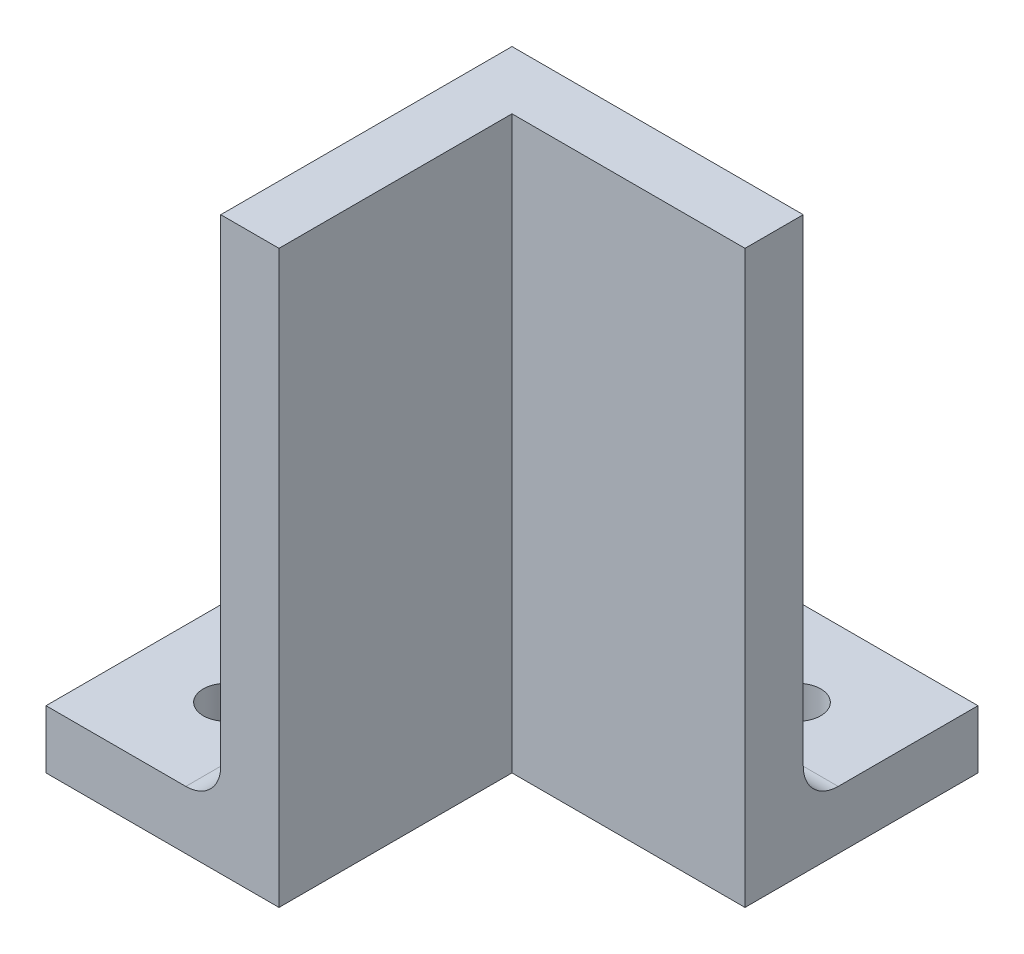
SolidWorks part; units mm, degrees
ref_plane "Front Plane" through (0, 0, 0) normal (0, 0, 1) x (1, 0, 0)
ref_plane "Top Plane" through (0, 0, 0) normal (0, 1, 0) x (1, 0, 0)
ref_plane "Right Plane" through (0, 0, 0) normal (1, 0, 0) x (0, 0, -1)
sketch "Sketch1" plane through (0, 0, 0) normal (0, 1, 0) x (1, 0, 0)
  line L0 (0, -20) -> (0, 0) construction
  line L1 (20, -20) -> (-20, -20) construction
  line L2 (20, -20) -> (20, 20) construction
  line L3 (20, 20) -> (-20, 20)
  line L4 (-20, -20) -> (-20, 20)
  line L5 (20, -20) -> (-20, 20) construction
  line L6 (20, 20) -> (-20, -20) construction
  line L7 (0, 0) -> (20, 0) construction
  line L8 (-20, -20) -> (0, -20)
  line L9 (0, -20) -> (0, 0)
  line L10 (0, 0) -> (20, 0)
  line L11 (20, 0) -> (20, 20)
  point P0 (0, 0)
  dimension "D1" = 40
  dimension "D2" = 40
extrude "Boss-Extrude1" add sketch "Sketch1" along normal blind 5
sketch "Sketch2" plane through (0, 5, 0) normal (0, 1, 0) x (1, 0, 0)
  line L1 (0, -20) -> (-5, -20)
  line L2 (0, -20) -> (0, 5)
  line L3 (0, 5) -> (-5, 5)
  line L4 (-5, -20) -> (-5, 5)
  line L5 (-5, 5) -> (20, 5)
  line L6 (-5, 5) -> (-5, 0)
  line L7 (-5, 0) -> (20, 0)
  line L8 (20, 5) -> (20, 0)
  line M4 (-20, -20) -> (0, -20)
  line M5 (0, -20) -> (0, 0)
  line M6 (0, 0) -> (20, 0)
  line M7 (20, 0) -> (20, 20)
  dimension "D1" = 5
  dimension "D2" = 25
extrude "Boss-Extrude2" add sketch "Sketch2" along normal blind 44 contours L7 L4 M4 M5 | L4 L7 L2 L3 | L5 L2 M6 M7
sketch "Sketch3" plane through (0, 5, 0) normal (0, 1, 0) x (1, 0, 0)
  line L0 (-12.5, -20) -> (-12.5, 20) construction
  line L2 (20, 20) -> (-20, 20) construction
  line L3 (-20, -20) -> (-5, -20) construction
  line L4 (-20, 20) -> (-20, -20) construction
  line L5 (-20, 12.5) -> (20, 12.5) construction
  line L6 (20, 5) -> (20, 20) construction
  circle A0 centre (-12.5, -12) radius 2
  circle A1 centre (-12.5, 12.5) radius 2
  circle A2 centre (12, 12.5) radius 2
  circle A3 centre (-12.5, 0) radius 2
  circle A4 centre (0, 12.5) radius 2
  dimension "D1" = 4
  dimension "D2" = 4
  dimension "D3" = 4
  dimension "D4" = 8
  dimension "D5" = 8
extrude "Cut-Extrude1" cut sketch "Sketch3" against normal through all
fillet "Fillet1" radius 3 2 edges at (7.5, 5, -5) (-5, 5, 7.5)
fillet "Fillet2" radius 3 1 edges at (-20, 2.5, -20)
